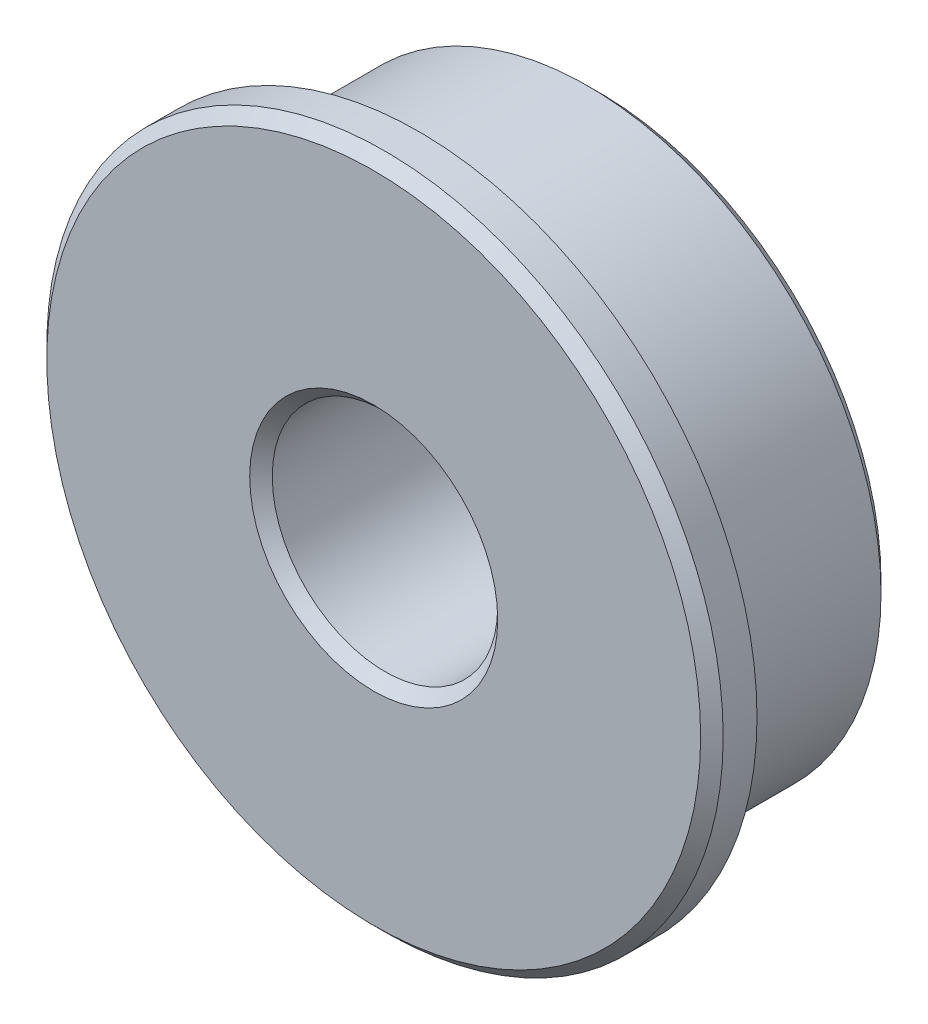
SolidWorks part; units mm, degrees
ref_plane "Front" through (0, 0, 0) normal (0, 0, 1) x (1, 0, 0)
ref_plane "Top" through (0, 0, 0) normal (0, 1, 0) x (1, 0, 0)
ref_plane "Right" through (0, 0, 0) normal (1, 0, 0) x (0, 0, -1)
sketch "Esquisse1" plane through (0, 0, 0) normal (0, 0, 1) x (1, 0, 0)
  circle A0 centre (0, 0) radius 2.5
  circle A1 centre (0, 0) radius 6.5
  dimension "D1" = 5
  dimension "D2" = 13
extrude "Boss.-Extru.1" add sketch "Esquisse1" along normal blind 5
sketch "Esquisse2" plane through (0, 0, 5) normal (0, 0, 1) x (1, 0, 0)
  circle A0 centre (0, 0) radius 7.5
  circle A1 centre (0, 0) radius 3
  dimension "D1" = 15
  dimension "D2" = 6
extrude "Boss.-Extru.2" add sketch "Esquisse2" against normal blind 1
chamfer "Chanfrein1" distance 0.25 angle 45 3 edges at (7.5, 0, 5) (2.5, 0, 5) (6.5, 0, 0)
